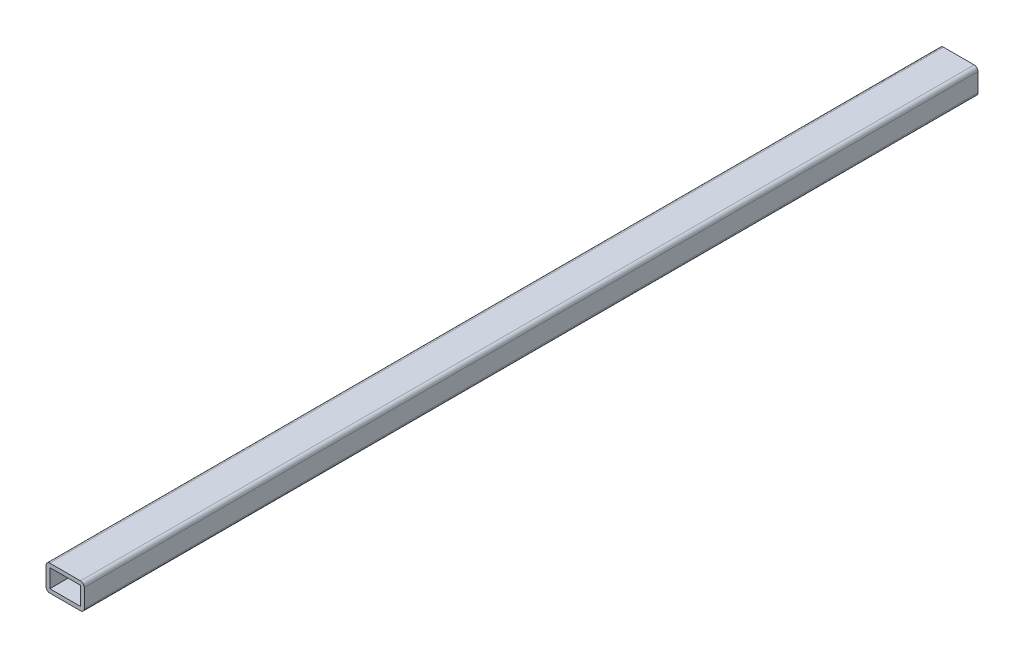
SolidWorks part; units mm, degrees
material "Gray Cast Iron"
ref_plane "Front Plane" through (0, 0, 0) normal (0, 0, 1) x (1, 0, 0)
ref_plane "Top Plane" through (0, 0, 0) normal (0, 1, 0) x (1, 0, 0)
ref_plane "Right Plane" through (0, 0, 0) normal (1, 0, 0) x (0, 0, -1)
sketch "Sketch1" plane through (0, 0, 0) normal (0, 0, 1) x (1, 0, 0)
  line L0 (3, 17.3315) -> (27, 17.3315)
  line L1 (3, 0) -> (27, 0)
  line L2 (0, 3) -> (0, 17.3315)
  line L3 (3, 20.3315) -> (27, 20.3315)
  line L4 (30, 3) -> (30, 17.3315)
  line L5 (27, 17.3315) -> (27, 3)
  line L6 (27, 3) -> (3, 3)
  line L7 (3, 3) -> (3, 17.3315)
  line L8 (0, 3) -> (0, 0) construction
  line L9 (3, 0) -> (-14.5846, 0) construction
  arc A0 (3, 20.3315) -> (0, 17.3315) centre (3, 17.3315) ccw
  arc A1 (30, 17.3315) -> (27, 20.3315) centre (27, 17.3315) ccw
  arc A2 (27, 0) -> (30, 3) centre (27, 3) ccw
  arc A3 (0, 3) -> (3, 0) centre (3, 3) ccw
  dimension "D1" = 3
  dimension "D2" = 3
  dimension "D3" = 3
  dimension "D6" = 3
  dimension "D4" = 24
  dimension "D5" = 14.3315
extrude "Boss-Extrude1" add sketch "Sketch1" along normal blind 700
